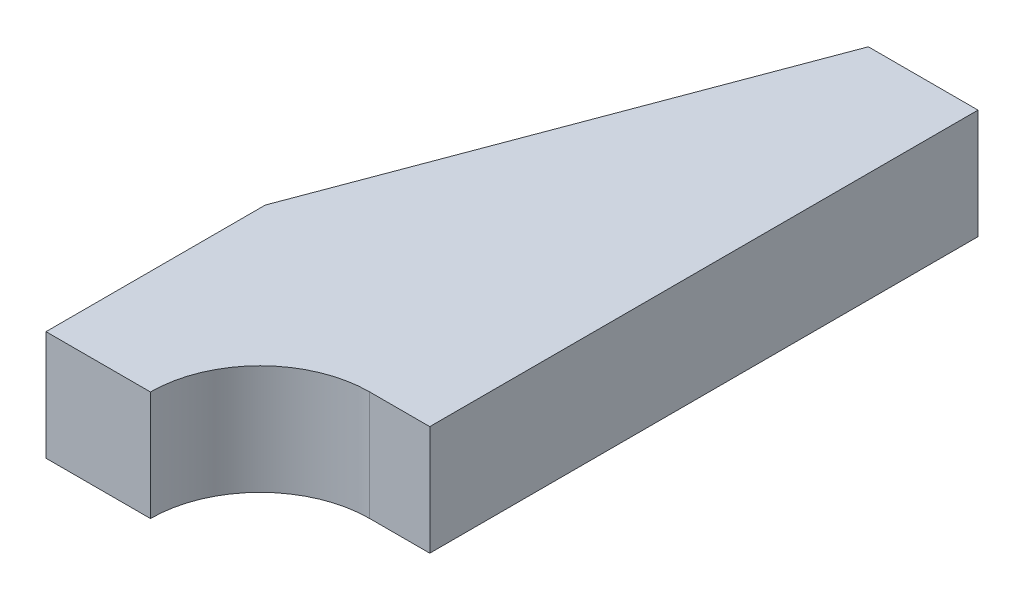
SolidWorks part; units mm, degrees
ref_plane "Alzado" through (0, 0, 0) normal (0, 0, 1) x (1, 0, 0)
ref_plane "Planta" through (0, 0, 0) normal (0, 1, 0) x (1, 0, 0)
ref_plane "Vista lateral" through (0, 0, 0) normal (1, 0, 0) x (0, 0, -1)
sketch "Croquis1" plane through (0, 0, 0) normal (0, 1, 0) x (1, 0, 0)
  line L0 (-12.5, 40) -> (12.5, -40) construction
  line L1 (-12.5, 40) -> (12.5, 40) construction
  line L2 (-12.5, 0) -> (-12.5, -20)
  line L3 (-12.5, -40) -> (12.5, -40) construction
  line L4 (12.5, 40) -> (12.5, -40) construction
  line L8 (7.025, -10) -> (12.5, -10)
  line L9 (12.5, -10) -> (12.5, 40)
  line L10 (12.5, 40) -> (2.5, 40)
  line L11 (2.5, 40) -> (-12.5, 0)
  line L12 (-2.975, -20) -> (-12.5, -20)
  arc A2 (-2.975, -20) -> (7.025, -10) centre (7.025, -20) cw
  dimension "D12" = 10
  dimension "D1" = 25
  dimension "D2" = 80
  dimension "D9" = 10
  dimension "D10" = 40
  dimension "D11" = 50
extrude "Saliente-Extruir1" add sketch "Croquis1" along normal blind 10
